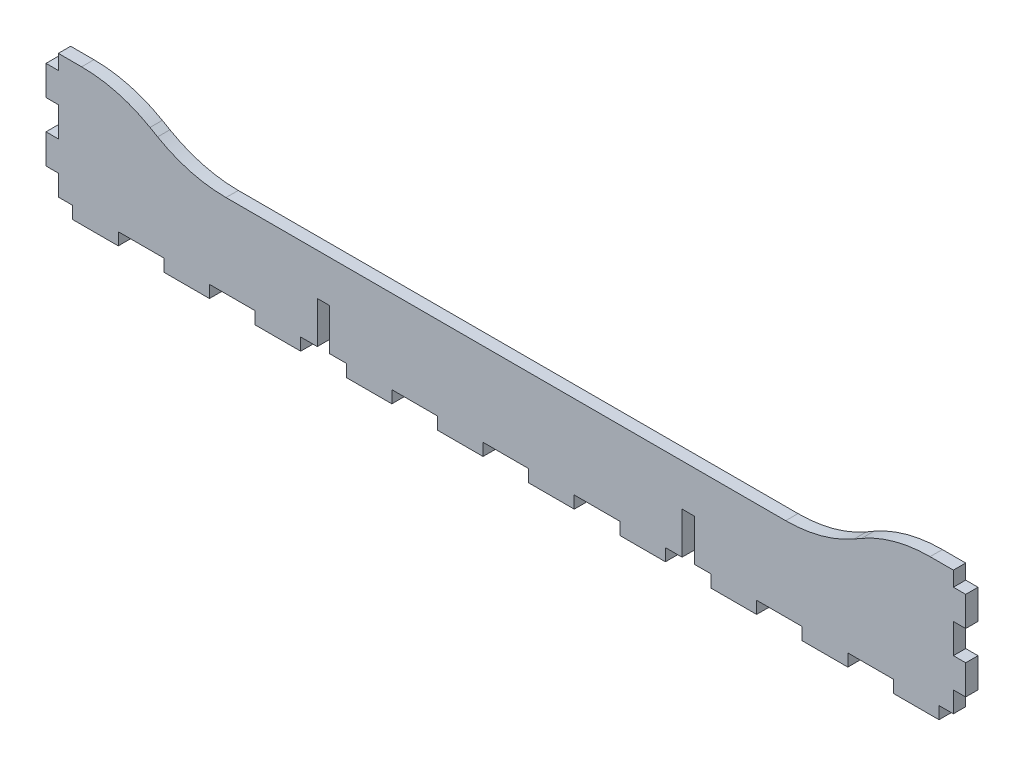
SolidWorks part; units mm, degrees
ref_plane "Plan de face" through (0, 0, 0) normal (0, 0, 1) x (1, 0, 0)
ref_plane "Plan de dessus" through (0, 0, 0) normal (0, 1, 0) x (1, 0, 0)
ref_plane "Plan de droite" through (0, 0, 0) normal (1, 0, 0) x (0, 0, -1)
sketch "Esquisse1" plane through (0, 0, 0) normal (0, 0, 1) x (1, 0, 0)
  line L1 (0, 0) -> (98.15, 0)
  line L2 (0, 0) -> (0, -27.3)
  line L3 (0, -27.3) -> (98.15, -27.3)
  line L4 (98.15, 0) -> (98.15, -27.3)
  dimension "D1" = 98.15
  dimension "38,3" = 27.3
extrude "Boss.-Extru.1" add sketch "Esquisse1" along normal blind 2.7
sketch "Esquisse2" plane through (0, 0, 0) normal (0, 0, 1) x (1, 0, 0)
  line L0 (0, -27.3) -> (98.15, -27.3) construction
  line L1 (5, -27.3) -> (15, -27.3)
  line L2 (5, -27.3) -> (5, -30)
  line L3 (5, -30) -> (15, -30)
  line L4 (15, -27.3) -> (15, -30)
  line L5 (10, -27.3) -> (10, -30) construction
  line L6 (0, 0) -> (0, -27.3) construction
  dimension "D1" = 10
  dimension "D2" = 10
  dimension "D3" = 2.7
extrude "Boss.-Extru.2" add sketch "Esquisse2" along normal blind 2.7
pattern_linear "Répétition linéaire1" count 5 spacing 20 along (1, 0, 0) of "Boss.-Extru.2"
sketch "Esquisse3" plane through (0, 0, 0) normal (0, 0, 1) x (1, 0, 0)
  line L0 (98.15, -27.3) -> (98.15, 0) construction
  line L1 (98.15, -3.25) -> (100.85, -3.25)
  line L2 (98.15, -3.25) -> (98.15, -9.75)
  line L3 (98.15, -9.75) -> (100.85, -9.75)
  line L4 (100.85, -3.25) -> (100.85, -9.75)
  line L5 (98.15, -6.5) -> (100.85, -6.5) construction
  line L6 (98.15, 0) -> (0, 0) construction
  dimension "D1" = 6.5
  dimension "D2" = 6.5
  dimension "D3" = 2.7
extrude "Boss.-Extru.3" add sketch "Esquisse3" along normal blind 2.7
pattern_linear "Répétition linéaire2" count 2 spacing 13 along (0, -1, 0) of "Boss.-Extru.3"
sketch "Esquisse4" plane through (0, 0, 0) normal (0, 0, 1) x (1, 0, 0)
  line L0 (0, -9) -> (69.4115, -9)
  line L1 (0, 0) -> (0, -27.3) construction
  line L2 (69.4115, -9) -> (85, 0)
  line L3 (98.15, 0) -> (0, 0) construction
  line L4 (85, 0) -> (0, 0)
  line L5 (0, 0) -> (0, -9)
  dimension "D1" = 30
  dimension "D2" = 85
  dimension "D3" = 9
extrude "Enlèv. mat.-Extru.1" cut sketch "Esquisse4" along normal blind 2.7
fillet "Congé1" radius 30 2 edges at (69.4115, -9, 1.35) (85, 0, 1.35)
mirror "Symétrie1" about plane through (0, 0, 0) normal (1, 0, 0) of bodies 107 105
sketch "Esquisse5" plane through (0, 0, 0) normal (0, 0, 1) x (1, 0, 0)
  line L0 (0, -9) -> (0, -27.3) construction
  line L1 (38.65, -18.15) -> (41.35, -18.15)
  line L2 (38.65, -18.15) -> (38.65, -27.3)
  line L3 (38.65, -27.3) -> (41.35, -27.3)
  line L4 (41.35, -18.15) -> (41.35, -27.3)
  line L5 (38.65, -18.15) -> (41.35, -27.3) construction
  line L6 (38.65, -27.3) -> (41.35, -18.15) construction
  line L8 (15, -27.3) -> (25, -27.3) construction
  line L9 (-61.3731, -9) -> (61.3731, -9) construction
  line L10 (-5, -27.3) -> (5, -27.3) construction
  line L11 (40, -18.15) -> (40, -27.3) construction
  line L12 (35, -27.3) -> (45, -27.3) construction
  point P0 (40, -22.725)
  point P14 (0, -18.15)
  dimension "D2" = 2.7
extrude "Enlèv. mat.-Extru.2" cut sketch "Esquisse5" along normal blind 2.7
mirror "Symétrie2" about plane through (0, 0, 0) normal (1, 0, 0) of "Enlèv. mat.-Extru.2"
sketch "Esquisse6" [suppressed] plane through (0, 0, 0) normal (0, 0, 1) x (1, 0, 0)
  line L0 (-20, -9) -> (-20, -27.3) construction
  line L2 (20.0026, -9) -> (20, -27.3) construction
  line L3 (-61.3731, -9) -> (61.3731, -9) construction
  line L4 (15, -27.3) -> (25, -27.3) construction
  line L5 (20.0013, -18.15) -> (-20, -18.15) construction
  line L6 (5, -30) -> (15, -30) construction
  line L7 (-21.35, -30) -> (-18.65, -30)
  line L8 (-21.35, -30) -> (-21.35, -18.15)
  line L9 (-21.35, -18.15) -> (-18.65, -18.15)
  line L10 (-18.65, -30) -> (-18.65, -18.15)
  line L12 (-15, -27.3) -> (-25, -27.3) construction
  point P17 (-20, -18.15)
  dimension "D1" = 2.7
extrude "Enlèv. mat.-Extru.3" [suppressed] cut sketch "Esquisse6" along normal blind 10
pattern_linear "Répétition linéaire3" [suppressed] count 2 spacing 40 count 2 spacing 40
